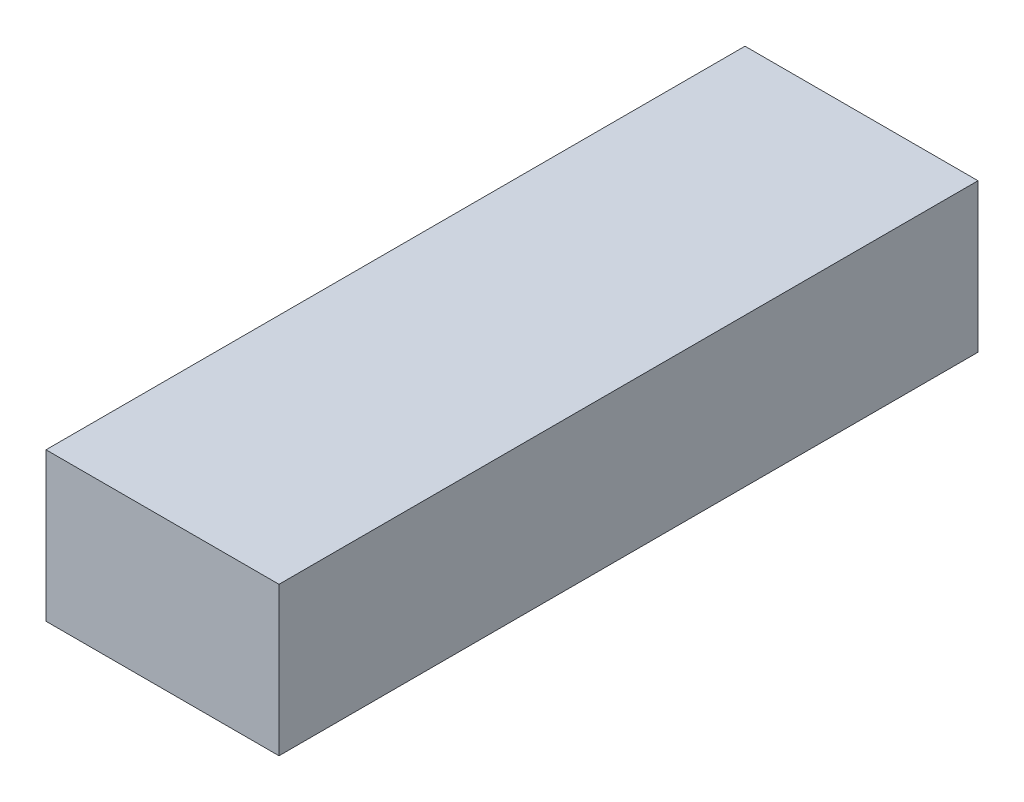
SolidWorks part; units mm, degrees
ref_plane "Plan de face" through (0, 0, 0) normal (0, 0, 1) x (1, 0, 0)
ref_plane "Plan de dessus" through (0, 0, 0) normal (0, 1, 0) x (1, 0, 0)
ref_plane "Plan de droite" through (0, 0, 0) normal (1, 0, 0) x (0, 0, -1)
sketch "Esquisse1" plane through (0, 0, 0) normal (0, 0, 1) x (1, 0, 0)
  line L1 (0, 0) -> (40, 0)
  line L2 (0, 0) -> (0, 25.5)
  line L3 (0, 25.5) -> (40, 25.5)
  line L4 (40, 0) -> (40, 25.5)
  dimension "D1" = 40
  dimension "D2" = 25.5
extrude "Boss.-Extru.1" add sketch "Esquisse1" along normal blind 120
